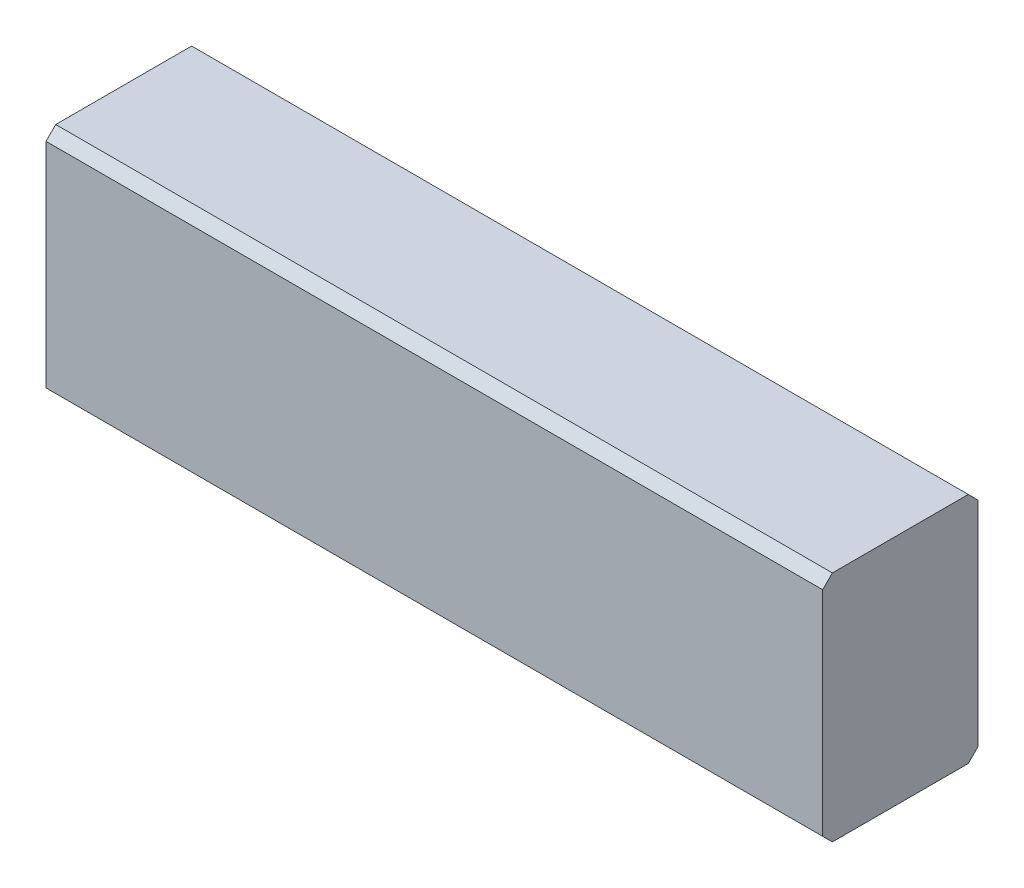
SolidWorks part; units mm, degrees
ref_plane "Front" through (0, 0, 0) normal (0, 0, 1) x (1, 0, 0)
ref_plane "Top" through (0, 0, 0) normal (0, 1, 0) x (1, 0, 0)
ref_plane "Right" through (0, 0, 0) normal (1, 0, 0) x (0, 0, -1)
other "Configuration Table"
sketch "Sketch1" plane through (0, 0, 0) normal (0, 0, 1) x (1, 0, 0)
  line L0 (0, 3) -> (-14, 3)
  line L1 (-14, -3) -> (0, -3)
  arc A0 (-14, 3) -> (-14, -3) centre (-14, 0) ccw
  arc A1 (0, -3) -> (0, 3) centre (0, 0) ccw
  dimension "b" = 6
  dimension "l" = 20
extrude "Extrude1" add sketch "Sketch1" along normal blind 4
sketch "Sketch2" plane through (0, 0, 0) normal (0, 0, 1) x (1, 0, 0)
  line L0 (0, 3) -> (-14, 3) construction
  line L1 (-17, 3) -> (3, 3)
  line L2 (-17, 3) -> (-17, -3)
  line L3 (-17, -3) -> (3, -3)
  line L4 (3, 3) -> (3, -3)
  line L5 (-14, -3) -> (0, -3) construction
  arc A0 (-14, 3) -> (-14, -3) centre (-14, 0) ccw construction
  arc A1 (0, -3) -> (0, 3) centre (0, 0) ccw construction
extrude "Extrude2" add sketch "Sketch2" along normal blind 4
sketch "Sketch3" plane through (0, 0, 0) normal (0, 0, 1) x (1, 0, 0)
  line L0 (-14, -3) -> (0, -3) construction
  line L1 (-14, -3) -> (3, -3)
  line L3 (-14, 3) -> (3, 3)
  line L4 (3, -3) -> (3, 3)
  arc A1 (-14, 3) -> (-14, -3) centre (-14, 0) ccw
  arc A2 (0, -3) -> (0, 3) centre (0, 0) ccw construction
  arc A3 (-14, 3) -> (-14, -3) centre (-14, 0) ccw construction
extrude "Extrude3" [suppressed] add sketch "Sketch3" along normal blind 4
chamfer "Chamfer1" distance 0.25 angle 45 8 edges at (-7, 3, 0) (-7, -3, 0) (-7, 3, 4) (-7, -3, 4) (3, 0, 0) (-17, 0, 0) (3, 0, 4) (-17, 0, 4)
equation "\"D1@Extrude2\" = \"h@Extrude1\""
equation "\"D1@Extrude3\" = \"h@Extrude1\""
